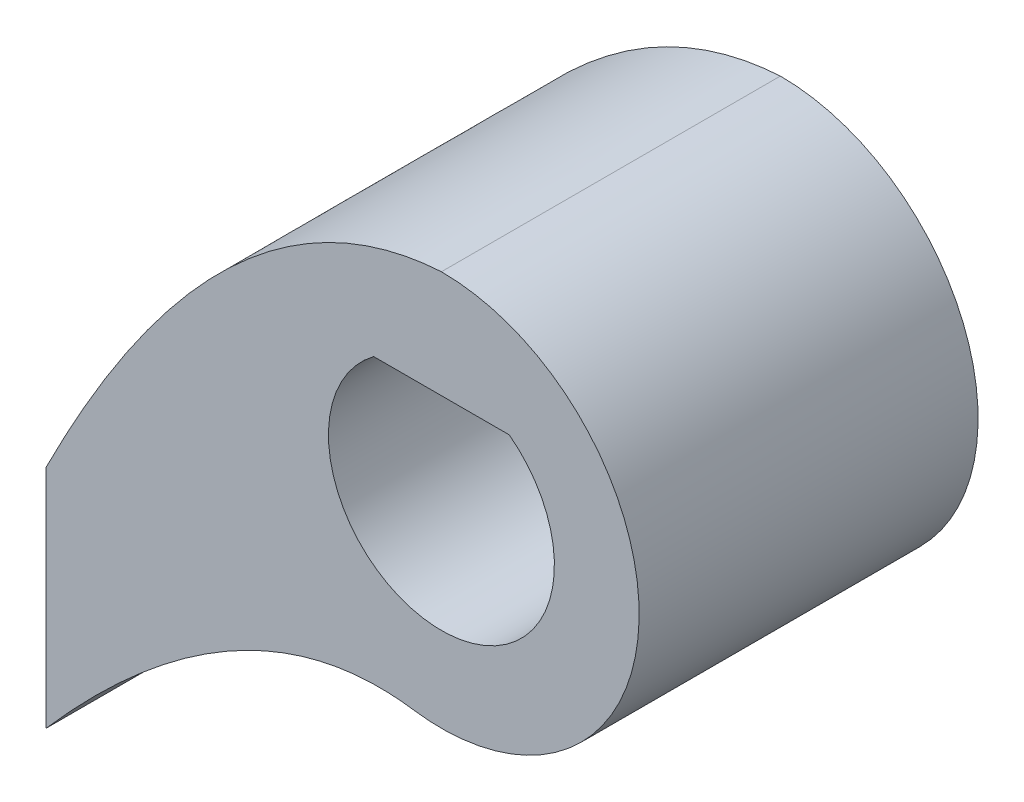
SolidWorks part; units mm, degrees
ref_plane "Vorne" through (0, 0, 0) normal (0, 0, 1) x (1, 0, 0)
ref_plane "Oben" through (0, 0, 0) normal (0, 1, 0) x (1, 0, 0)
ref_plane "Seite" through (0, 0, 0) normal (1, 0, 0) x (0, 0, -1)
sketch "Skizze1" plane through (0, 0, 0) normal (0, 0, 1) x (1, 0, 0)
  line L0 (-7, -7) -> (-7, -3)
  line L1 (1.2, 1.6) -> (-1.2, 1.6)
  arc A0 (-1.2, 1.6) -> (1.2, 1.6) centre (0, 0) ccw
  arc A1 (-0.5, -3.4641) -> (0, 3.5) centre (0, 0) ccw
  spline S0 degree 2 poles (-7, -3) (-3.8464, 3.2713) (0, 3.5) knots 0 0 0 0.663529 0.663529 0.663529
  spline S1 degree 2 poles (-7, -7) (-3.5334, -3.0263) (-0.5, -3.4641) knots 0 0 0 0.361848 0.361848 0.361848
  dimension "D3" = 4
  dimension "D4" = 3.5
  dimension "D5" = 4
  dimension "D1" = 7
  dimension "D2" = 7
  dimension "D6" = 0.5
  dimension "D7" = 1.6
extrude "Aufsatz-Linear austragen1" add sketch "Skizze1" along normal blind 6
